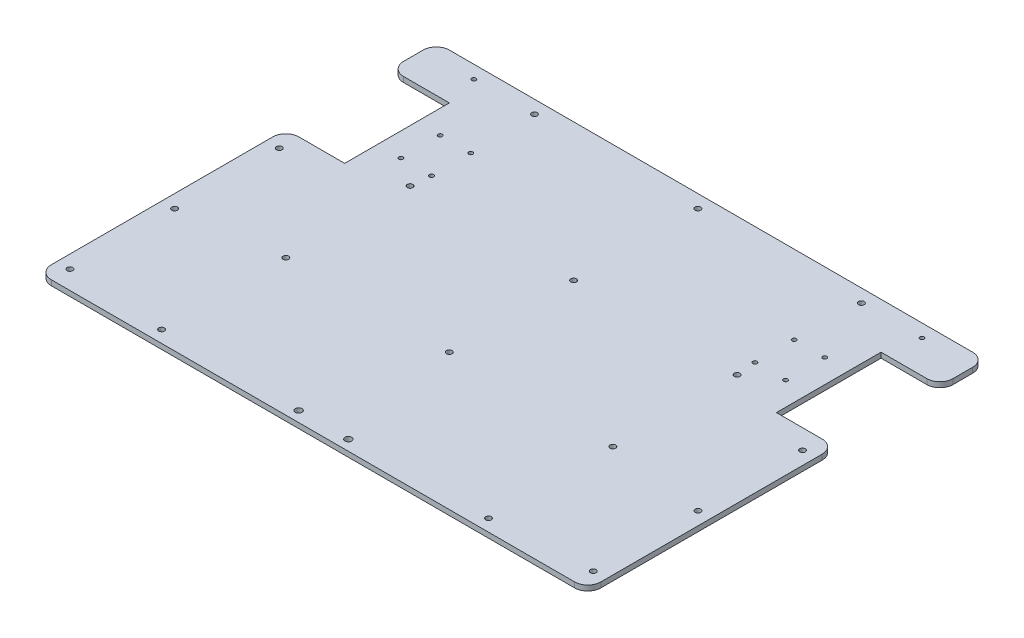
SolidWorks part; units mm, degrees
material "1060 合金"
ref_plane "前视基准面" through (0, 0, 0) normal (0, 0, 1) x (1, 0, 0)
ref_plane "上视基准面" through (0, 0, 0) normal (0, 1, 0) x (1, 0, 0)
ref_plane "右视基准面" through (0, 0, 0) normal (1, 0, 0) x (0, 0, -1)
other "Configuration Table"
sketch "草图1" plane through (0, 0, 0) normal (0, 1, 0) x (1, 0, 0)
  line L0 (0, -152.1) -> (0, -144.1) construction
  line L1 (210, 152.1) -> (-210, 152.1)
  line L2 (210, 152.1) -> (210, -152.1)
  line L3 (210, -152.1) -> (-210, -152.1)
  line L4 (-210, 152.1) -> (-210, -152.1)
  line L5 (210, 152.1) -> (-210, -152.1) construction
  line L6 (210, -152.1) -> (-210, 152.1) construction
  line L7 (-19, -144.1) -> (19, -144.1) construction
  circle A0 centre (-19, -144.1) radius 2.55
  circle A1 centre (19, -144.1) radius 2.55
  point P0 (0, 0)
  point P10 (0, -144.1)
  dimension "D5" = 5.1
  dimension "D1" = 420
  dimension "D2" = 304.2
  dimension "D3" = 8
  dimension "D4" = 38
extrude "凸台-拉伸1" add sketch "草图1" along normal blind 4
sketch "草图2" plane through (0, 0, 0) normal (0, 1, 0) x (1, 0, 0)
  line L0 (0, 0) -> (0, 77.1) construction
  line L1 (0, 77.1) -> (-187.5, 77.1) construction
  line L2 (-210, 152.1) -> (-210, -152.1) construction
  line L3 (-165, 117.1) -> (-210, 117.1)
  line L4 (-165, 117.1) -> (-165, 37.1)
  line L5 (-165, 37.1) -> (-210, 37.1)
  line L6 (-210, 117.1) -> (-210, 37.1)
  line L7 (-165, 117.1) -> (-210, 37.1) construction
  line L8 (-165, 37.1) -> (-210, 117.1) construction
  line L9 (210, 152.1) -> (-210, 152.1) construction
  line L10 (-147, 92.1) -> (-123.6, 92.1) construction
  line L11 (-147, 92.1) -> (-147, 62.1) construction
  line L12 (-147, 62.1) -> (-123.6, 62.1) construction
  line L13 (-123.6, 92.1) -> (-123.6, 62.1) construction
  line L14 (-147, 92.1) -> (-123.6, 62.1) construction
  line L15 (-147, 62.1) -> (-123.6, 92.1) construction
  circle A0 centre (-147, 92.1) radius 1.6
  circle A1 centre (-147, 62.1) radius 1.6
  circle A2 centre (-123.6, 62.1) radius 1.6
  circle A3 centre (-123.6, 92.1) radius 1.6
  point P12 (-135.3, 77.1)
  dimension "D6" = 3.2
  dimension "D1" = 45
  dimension "D2" = 80
  dimension "D3" = 75
  dimension "D4" = 23.4
  dimension "D5" = 30
  dimension "D7" = 18
extrude "切除-拉伸1" cut sketch "草图2" along normal through all
mirror "镜向1" about plane through (0, 0, 0) normal (1, 0, 0) of "切除-拉伸1"
sketch "草图3" plane through (0, 0, 0) normal (0, 1, 0) x (1, 0, 0)
  line L0 (0, 0) -> (0, 137.1) construction
  line L3 (40, 137.1) -> (-40, 137.1) construction
  line L4 (210, 152.1) -> (-210, 152.1) construction
  circle A4 centre (-40, 137.1) radius 2.15
  circle A5 centre (40, 137.1) radius 2.15
  point P7 (0, 137.1)
  dimension "D3" = 4.3
  dimension "D2" = 80
  dimension "D1" = 15
sketch "草图4" plane through (0, 0, 0) normal (0, 1, 0) x (1, 0, 0)
  line L0 (0, 0) -> (0, 142.1) construction
  line L1 (125, 142.1) -> (-125, 142.1) construction
  line L3 (210, 152.1) -> (-210, 152.1) construction
  circle A5 centre (-125, 142.1) radius 2.15
  circle A6 centre (125, 142.1) radius 2.15
  circle A7 centre (0, 142.1) radius 2.15
  point P6 (0, 142.1)
  point P9 (0, 142.1)
  dimension "D3" = 4.3
  dimension "D1" = 10
  dimension "D2" = 250
extrude "切除-拉伸3" cut sketch "草图4" along normal through all
pattern_linear "阵列(线性)3" count 4 spacing 95 along (0, 0, 1) of "切除-拉伸3"
sketch "草图7" plane through (0, 0, 0) normal (0, 1, 0) x (1, 0, 0)
  line L0 (200, 22.1) -> (-200, 22.1) construction
  line L1 (200, 22.1) -> (200, -137.9) construction
  line L2 (200, -137.9) -> (-200, -137.9) construction
  line L3 (-200, 22.1) -> (-200, -137.9) construction
  line L4 (200, 22.1) -> (-200, -137.9) construction
  line L5 (200, -137.9) -> (-200, 22.1) construction
  line L6 (171.25, 142.1) -> (-171.25, 142.1) construction
  line L7 (171.25, 142.1) -> (171.25, -257.9) construction
  line L8 (171.25, -257.9) -> (-171.25, -257.9) construction
  line L9 (-171.25, 142.1) -> (-171.25, -257.9) construction
  line L10 (171.25, 142.1) -> (-171.25, -257.9) construction
  line L11 (171.25, -257.9) -> (-171.25, 142.1) construction
  line L12 (0, 0) -> (0, -50000) construction
  line L13 (210, 152.1) -> (-210, 152.1) construction
  circle A0 centre (-200, 22.1) radius 2.15
  circle A1 centre (-200, -137.9) radius 2.15
  circle A2 centre (-200, -57.9) radius 2.15
  circle A3 centre (200, -57.9) radius 2.15
  circle A4 centre (200, 22.1) radius 2.15
  circle A5 centre (200, -137.9) radius 2.15
  circle A6 centre (-171.25, 142.1) radius 1.6
  circle A7 centre (171.25, 142.1) radius 1.6
  circle A8 centre (171.25, -257.9) radius 1.6
  circle A9 centre (-171.25, -257.9) radius 1.6
  point P0 (0, -57.9)
  point P14 (0, -57.9)
  dimension "D3" = 4.3
  dimension "D4" = 3.2
  dimension "D1" = 400
  dimension "D2" = 160
  dimension "D5" = 342.5
  dimension "D6" = 210
  dimension "D7" = 10
extrude "切除-拉伸5" cut sketch "草图7" along normal through all
sketch "草图9" plane through (0, 0, 0) normal (0, 1, 0) x (1, 0, 0)
  circle A0 centre (0, -142.9) radius 2.15
extrude "凸台-拉伸2" add sketch "草图9" along normal through all
fillet "圆角1" radius 10 8 edges at (210, 2, -152.1) (210, 2, -117.1) (210, 2, -37.1) (210, 2, 152.1) (-210, 2, 152.1) (-210, 2, -37.1) (-210, 2, -117.1) (-210, 2, -152.1)
